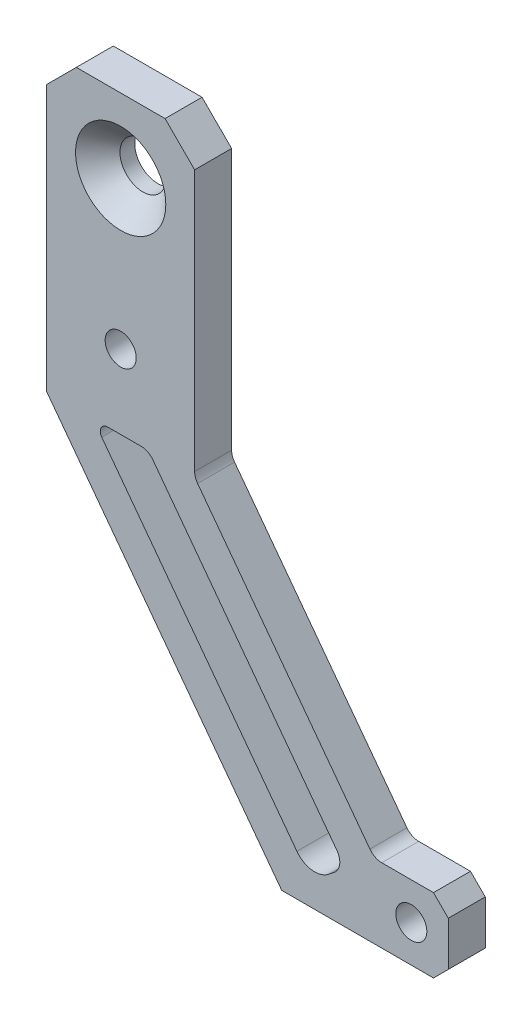
SolidWorks part; units mm, degrees
ref_plane "前视基准面" through (0, 0, 0) normal (0, 0, 1) x (1, 0, 0)
ref_plane "上视基准面" through (0, 0, 0) normal (0, 1, 0) x (1, 0, 0)
ref_plane "右视基准面" through (0, 0, 0) normal (1, 0, 0) x (0, 0, -1)
sketch "草图1" plane through (0, 0, 0) normal (0, 0, 1) x (1, 0, 0)
  line L0 (-10, 10) -> (-10, -30)
  line L1 (-10, -30) -> (21.7769, -72.5)
  line L2 (21.7769, -72.5) -> (44.3, -72.5)
  line L3 (44.3, -72.5) -> (44.3, -62.5)
  line L4 (44.3, -62.5) -> (34.3, -62.5)
  line L5 (34.3, -62.5) -> (10, -30)
  line L6 (10, -30) -> (10, 10)
  line L7 (10, 10) -> (-10, 10)
  line L8 (-3.7569, -30) -> (3.7569, -30)
  line L9 (25.6861, -69.3785) -> (30.3909, -65.6215)
  line L10 (-3.7569, -30) -> (25.6861, -69.3785)
  line L11 (30.3909, -65.6215) -> (3.7569, -30)
  line L12 (30.2956, -65.4941) -> (5.9956, -32.9941) construction
  line L13 (-5.9956, -27.0059) -> (25.7814, -69.5059) construction
  circle A0 centre (39.3, -67.5) radius 2.1
  circle A1 centre (0, 0) radius 3.1
  point P10 (0, 10)
  dimension "D1" = 4.2
  dimension "D2" = 39.3
  dimension "D3" = 6.2
  dimension "D5" = 10
  dimension "D7" = 5
  dimension "D8" = 5
  dimension "D12" = 67.5
  dimension "D4" = 10
  dimension "D6" = 20
  dimension "D9" = 10
  dimension "D10" = 40
  dimension "D11" = 10
  dimension "D13" = 5
extrude "凸台-拉伸1" add sketch "草图1" along normal mid plane 5
fillet "圆角1" radius 2 4 edges at (34.3, -62.5, 0) (10, -30, 0) (3.7569, -30, 0) (30.3909, -65.6215, 0)
fillet "圆角2" radius 3 1 edges at (25.6861, -69.3785, 0)
chamfer "倒角1" distance 4 angle 45 2 edges at (10, 10, 0) (-10, 10, 0)
chamfer "倒角2" distance 2 angle 45 2 edges at (44.3, -72.5, 0) (44.3, -62.5, 0)
fillet "圆角3" radius 1 1 edges at (-3.7569, -30, 0)
sketch "草图2" plane through (0, 0, 2.5) normal (0, 0, 1) x (1, 0, 0)
  circle A0 centre (0, -20) radius 2.1
  circle A1 centre (0, 0) radius 3.1 construction
  dimension "D1" = 4.2
  dimension "D2" = 20
extrude "切除-拉伸1" cut sketch "草图2" against normal blind 5
chamfer "倒角3" distance 3 angle 45 1 edges at (3.1, 0, 2.5)
